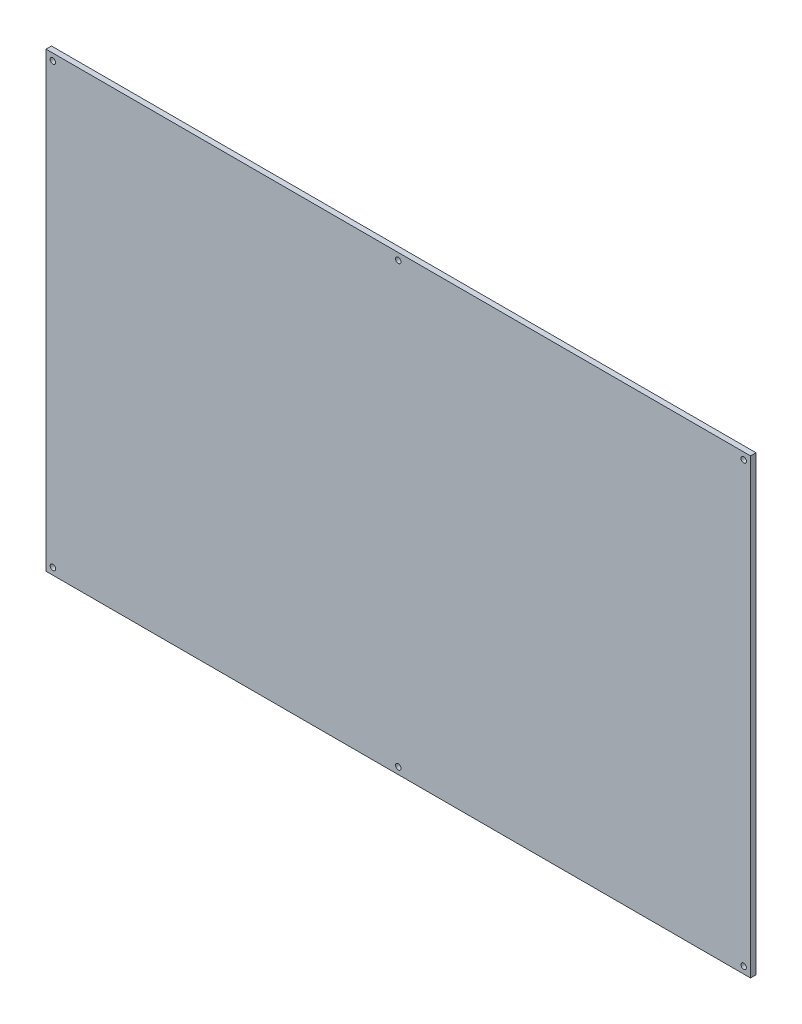
SolidWorks part; units mm, degrees
ref_plane "Plan de face" through (0, 0, 0) normal (0, 0, 1) x (1, 0, 0)
ref_plane "Plan de dessus" through (0, 0, 0) normal (0, 1, 0) x (1, 0, 0)
ref_plane "Plan de droite" through (0, 0, 0) normal (1, 0, 0) x (0, 0, -1)
sketch "Esquisse1" plane through (0, 0, 0) normal (0, 0, 1) x (1, 0, 0)
  line L1 (-69.8345, 33.8315) -> (188.6155, 33.8315)
  line L2 (-69.8345, 33.8315) -> (-69.8345, -132.0685)
  line L3 (-69.8345, -132.0685) -> (188.6155, -132.0685)
  line L4 (188.6155, 33.8315) -> (188.6155, -132.0685)
  circle A0 centre (-67.3345, 31.3315) radius 1
  circle A1 centre (59.3855, 31.3315) radius 1
  circle A2 centre (186.1155, 31.3315) radius 1
  circle A3 centre (-67.3345, -129.5685) radius 1
  circle A4 centre (59.3855, -129.5685) radius 1
  circle A5 centre (186.1155, -129.5685) radius 1
  dimension "D3" = 2.5
  dimension "D1" = 258.45
  dimension "D2" = 165.9
  dimension "D4" = 2.5
  dimension "D5" = 2.5
  dimension "D6" = 2.5
  dimension "D7" = 2.5
  dimension "D8" = 2.5
  dimension "D9" = 2.5
  dimension "D10" = 2.5
  dimension "D11" = 2.5
  dimension "D12" = 2.5
  dimension "D13" = 129.22
  dimension "D14" = 129.22
extrude "Boss.-Extru.1" add sketch "Esquisse1" along normal blind 2
